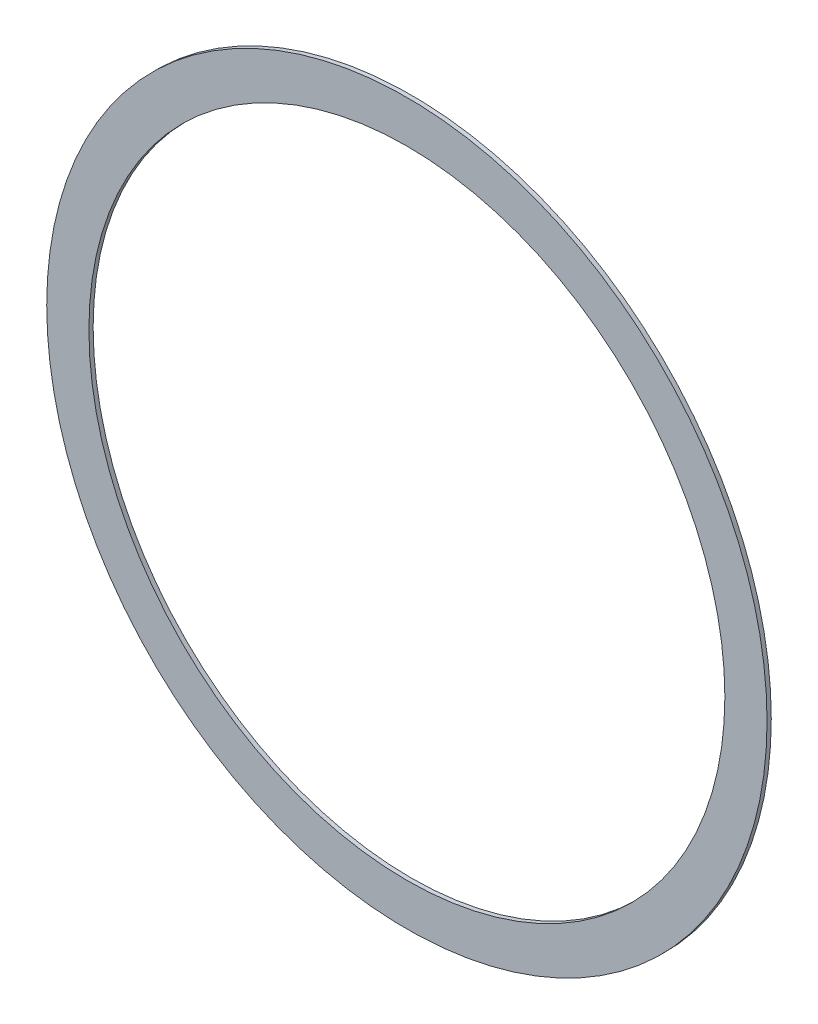
SolidWorks part; units mm, degrees
ref_plane "Front Plane" through (0, 0, 0) normal (0, 0, 1) x (1, 0, 0)
ref_plane "Top Plane" through (0, 0, 0) normal (0, 1, 0) x (1, 0, 0)
ref_plane "Right Plane" through (0, 0, 0) normal (1, 0, 0) x (0, 0, -1)
sketch "Sketch1" plane through (0, 0, 0) normal (0, 0, 1) x (1, 0, 0)
  circle A0 centre (0, 0) radius 15
  circle A1 centre (0, 0) radius 16.99
  dimension "D1" = 30
  dimension "D2" = 33.98
extrude "Boss-Extrude1" add sketch "Sketch1" along normal blind 0.2
scale "Scale1" scale about centroid uniform scaling yes scale factor 1.9329
scale "Scale2" scale about centroid uniform scaling yes scale factor 1.5
